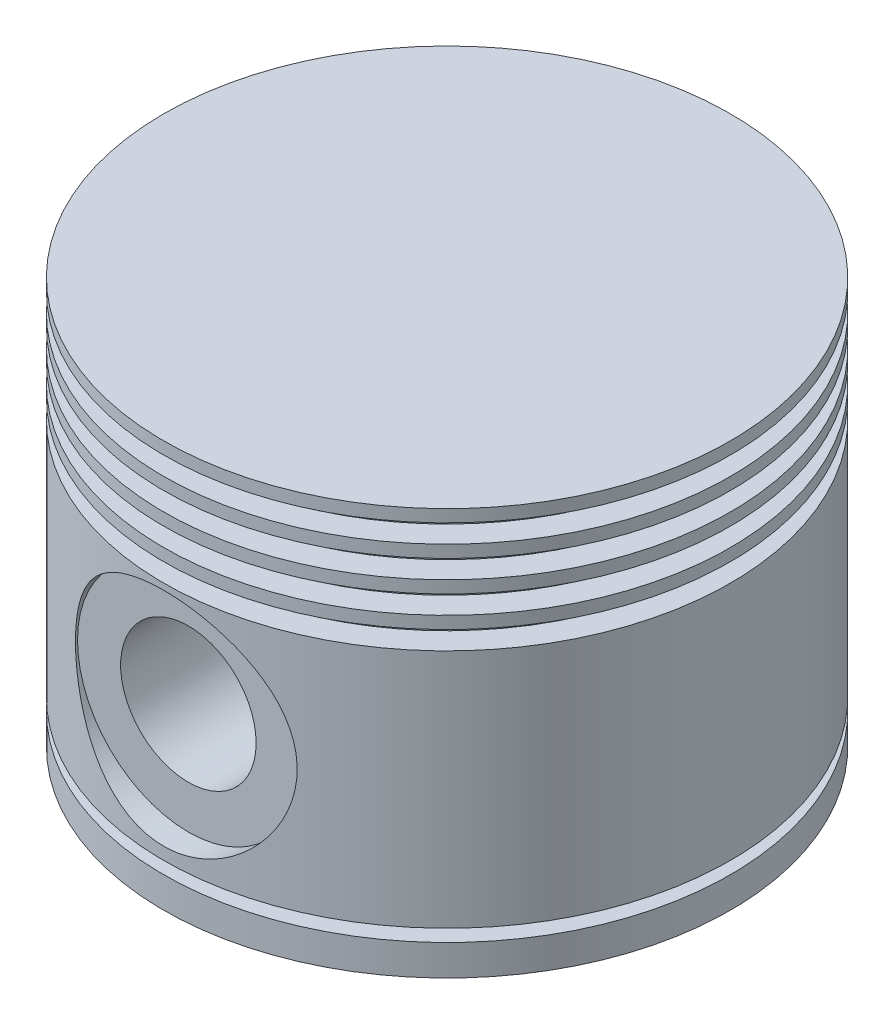
SolidWorks part; units mm, degrees
material "1.5805 (10NiCr5-4)"
ref_plane "Front Plane" through (0, 0, 0) normal (0, 0, 1) x (1, 0, 0)
ref_plane "Top Plane" through (0, 0, 0) normal (0, 1, 0) x (1, 0, 0)
ref_plane "Right Plane" through (0, 0, 0) normal (1, 0, 0) x (0, 0, -1)
sketch "Sketch1" plane through (0, 0, 0) normal (0, 0, 1) x (1, 0, 0)
  line L0 (0, 66) -> (0, -66) construction
  line L1 (-46, 0) -> (-37, 0) construction
  line L2 (0, 66) -> (-46, 66)
  line L3 (-46, 66) -> (-46, 64)
  line L4 (-46, 64) -> (-42, 64)
  line L5 (-42, 64) -> (-42, 61)
  line L6 (-42, 61) -> (-46, 61)
  line L7 (-46, 61) -> (-46, 59)
  line L8 (-46, 59) -> (-42, 59)
  line L9 (-42, 59) -> (-42, 56)
  line L10 (-42, 56) -> (-46, 56)
  line L11 (-46, 56) -> (-46, 54)
  line L12 (-46, 54) -> (-42, 54)
  line L13 (-42, 54) -> (-42, 51)
  line L14 (-42, 51) -> (-46, 51)
  line L15 (-46, 46) -> (-46, 7)
  line L16 (-46, 49) -> (-42, 49)
  line L17 (-42, 49) -> (-42, 46)
  line L18 (-42, 46) -> (-46, 46)
  line L19 (-46, 51) -> (-46, 49)
  line L20 (-46, 5) -> (-46, 0)
  line L21 (-46, 7) -> (-42, 7)
  line L22 (-46, 5) -> (-42, 5)
  line L23 (-42, 7) -> (-42, 5)
  line L24 (0, 62) -> (-37.464, 62)
  line L25 (-37.464, 62) -> (-37, 46.0164)
  line L26 (-46, 0) -> (-37, 0)
  line L27 (-37, 7) -> (-37, 0)
  line L29 (0, 66) -> (0, 62)
  line L30 (-37, 46.0164) -> (-37, 7)
  point P3 (0, 0)
  point P5 (0, 0)
  dimension "D1" = 46
  dimension "D2" = 66
  dimension "D3" = 2
  dimension "D4" = 3
  dimension "D5" = 2
  dimension "D6" = 3
  dimension "D7" = 2
  dimension "D8" = 3
  dimension "D9" = 2
  dimension "D10" = 3
  dimension "D11" = 4
  dimension "D12" = 7
  dimension "D13" = 2
  dimension "D14" = 62
  dimension "D16" = 39
revolve "Revolve1" add sketch "Sketch1" angle 360 about L0
sketch "Sketch2" plane through (0, 0, 0) normal (0, 0, 1) x (1, 0, 0)
  circle A0 centre (0, 27) radius 11
  dimension "D1" = 22
  dimension "D2" = 27
extrude "Cut-Extrude1" cut sketch "Sketch2" against normal through all both and the other way through all
sketch "Sketch3" plane through (0, 0, 0) normal (0, 0, 1) x (1, 0, 0)
  circle A0 centre (0, 27) radius 18
  dimension "D1" = 36
extrude "Cut-Extrude3" cut sketch "Sketch3" against normal blind 4 and the other way blind 4 from offset 46
mirror "Mirror2" about plane through (0, 0, 0) normal (0, 0, 1) of "Cut-Extrude3"
sketch "Sketch6" plane through (0, 0, 0) normal (0, 0, 1) x (1, 0, 0)
  circle A0 centre (0, 27) radius 11
  circle A1 centre (0, 27) radius 18
extrude "Boss-Extrude2" add sketch "Sketch6" along normal up to surface (10.327 mm away) from offset 25
mirror "Mirror4" about plane through (0, 0, 0) normal (0, 0, 1) of "Boss-Extrude2"
